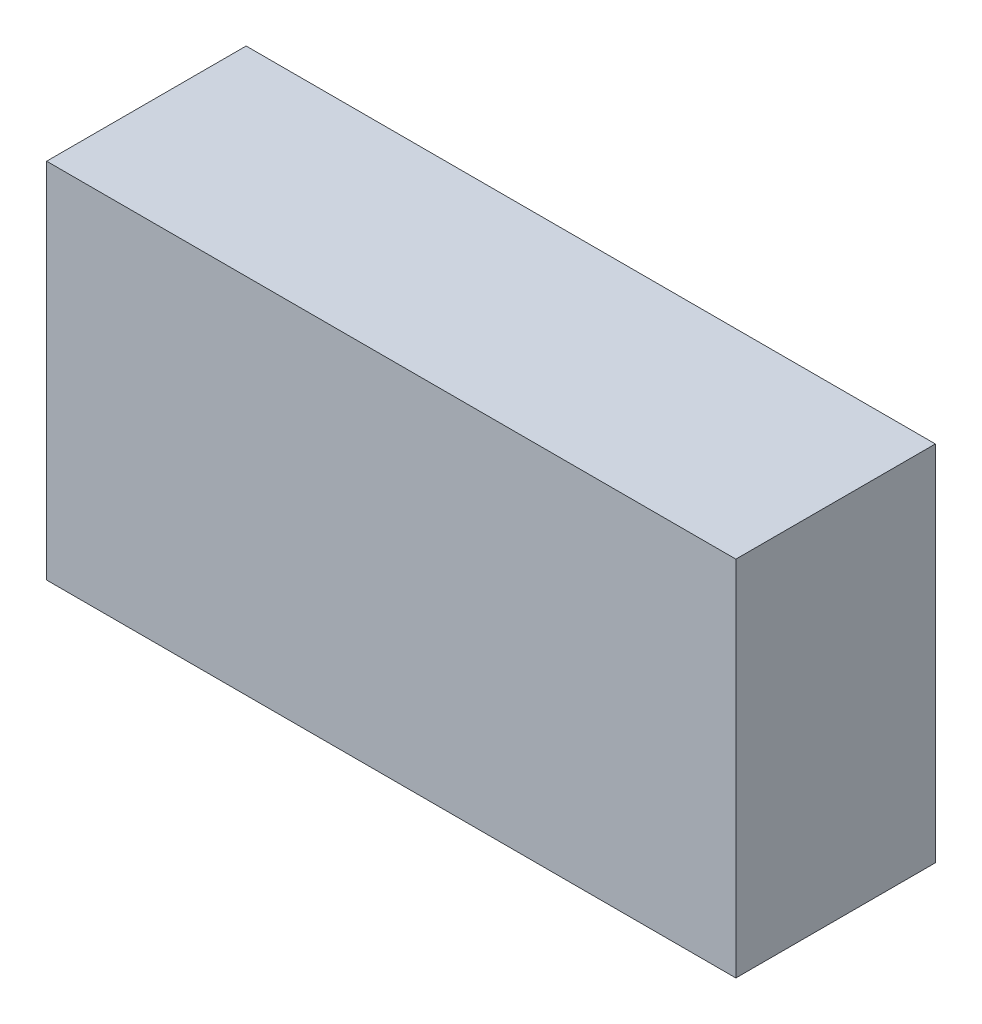
SolidWorks part; units mm, degrees
ref_plane "前视基准面" through (0, 0, 0) normal (0, 0, 1) x (1, 0, 0)
ref_plane "上视基准面" through (0, 0, 0) normal (0, 1, 0) x (1, 0, 0)
ref_plane "右视基准面" through (0, 0, 0) normal (1, 0, 0) x (0, 0, -1)
sketch "草图1" plane through (0, 0, 0) normal (0, 0, 1) x (1, 0, 0)
  line L1 (0, 0) -> (38, 0)
  line L2 (0, 0) -> (0, -20)
  line L3 (0, -20) -> (38, -20)
  line L4 (38, 0) -> (38, -20)
  dimension "D1" = 38
  dimension "D2" = 20
extrude "凸台-拉伸1" add sketch "草图1" along normal blind 11
